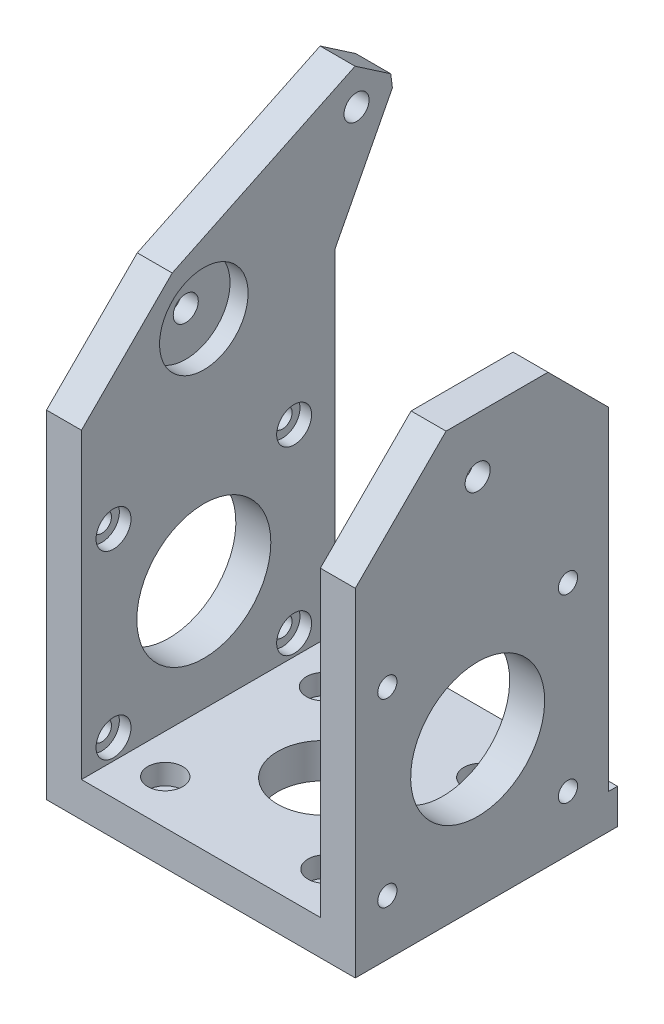
SolidWorks part; units mm, degrees
ref_plane "前视基准面" through (0, 0, 0) normal (0, 0, 1) x (1, 0, 0)
ref_plane "上视基准面" through (0, 0, 0) normal (0, 1, 0) x (1, 0, 0)
ref_plane "右视基准面" through (0, 0, 0) normal (1, 0, 0) x (0, 0, -1)
sketch "草图1" plane through (0, 0, 0) normal (0, 0, 1) x (1, 0, 0)
  line L0 (0, 69.1122) -> (0, -33.2959) construction
  line L1 (-20.5, 73.5) -> (-26.5, 73.5)
  line L2 (-26.5, 73.5) -> (-26.5, 0)
  line L3 (-26.5, 0) -> (26.5, 0)
  line L4 (-20.5, 73.5) -> (-20.5, 6)
  line L5 (-20.5, 6) -> (20.5, 6)
  line L6 (20.5, 73.5) -> (20.5, 6)
  line L7 (26.5, 73.5) -> (26.5, 0)
  line L8 (20.5, 73.5) -> (26.5, 73.5)
  point P10 (0, 6)
  point P12 (0, 0)
  dimension "D1" = 53
  dimension "D2" = 73.5
  dimension "D3" = 6
  dimension "D4" = 6
  dimension "D5" = 41
extrude "凸台-拉伸1" add sketch "草图1" along normal blind 64
sketch "草图2" plane through (0, 6, 0) normal (0, 1, 0) x (1, 0, 0)
  line L0 (0, -64) -> (0, 9.0093) construction
  line L1 (20.5, -64) -> (-20.5, -64) construction
  line L2 (-37.6795, -29.6523) -> (44.7155, -30.4126) construction
  circle A0 centre (0, -30) radius 7.85
  circle A1 centre (-13.5, -16.3749) radius 1.65
  circle A2 centre (-13.7491, -43.3737) radius 1.65
  circle A3 centre (13.7491, -43.3737) radius 1.65
  circle A4 centre (13.5, -16.3749) radius 1.65
  dimension "D1" = 34
  dimension "D2" = 15.7
  dimension "D3" = 27
  dimension "D4" = 3.3
  dimension "D5" = 27
extrude "切除-拉伸1" cut sketch "草图2" against normal blind 20
sketch "草图3" plane through (0, 6, 0) normal (0, 1, 0) x (1, 0, 0)
  circle A0 centre (-13.5, -16.3749) radius 3
  circle A1 centre (13.5, -16.3749) radius 3
  circle A2 centre (13.7491, -43.3737) radius 3
  circle A3 centre (-13.7491, -43.3737) radius 3
  dimension "D1" = 6
extrude "切除-拉伸2" cut sketch "草图3" against normal blind 3.5
sketch "草图4" plane through (26.5, 0, 0) normal (1, 0, 0) x (0, 0, -1)
  line L1 (-64, 0) -> (-64, 73.5) construction
  line L4 (-51, 0) -> (-51, 57.9226)
  line L5 (-51, 57.9226) -> (-35.4226, 73.5)
  line L6 (-64, 73.5) -> (0, 73.5) construction
  line L7 (-35.4226, 73.5) -> (-17.9226, 73.5)
  line L8 (-17.9226, 73.5) -> (-7.5, 63.0774)
  line L9 (-6, 6) -> (-6, 0)
  line L10 (-7.5, 63.0774) -> (-7.5, 6)
  line L11 (-64, 0) -> (0, 0) construction
  line L13 (0, 0) -> (0, 73.5)
  line L14 (0, 0) -> (0, 73.5) construction
  line L15 (0, 73.5) -> (-17.9226, 73.5)
  line L16 (-64, 0) -> (-64, 73.5)
  line L17 (-64, 73.5) -> (-35.4226, 73.5)
  line L23 (-6, 0) -> (0, 0)
  line L25 (-53.2092, 0) -> (-64, 0)
  line L26 (-6, 6) -> (-7.5, 6)
  dimension "D1" = 13
  dimension "D6" = 43.5
  dimension "D7" = 17.5
  dimension "D8" = 45
  dimension "D9" = 45
  dimension "D10" = 28.5774
extrude "切除-拉伸3" cut sketch "草图4" against normal through all
sketch "草图5" plane through (26.5, 0, 0) normal (1, 0, 0) x (0, 0, -1)
  line L0 (-51, 0) -> (-51, 57.9226) construction
  line L1 (-51, 0) -> (-6, 0) construction
  line L2 (-30, 72.1014) -> (-30, -4.8717) construction
  line L3 (-57.7657, 25) -> (11.8561, 25) construction
  line L4 (-35.4226, 73.5) -> (-17.9226, 73.5) construction
  circle A0 centre (-30, 25) radius 11.5
  circle A1 centre (-45.5, 9.5) radius 1.65
  circle A2 centre (-14.5, 9.5) radius 1.65
  circle A3 centre (-14.5, 40.5) radius 1.65
  circle A4 centre (-45.5, 40.5) radius 1.65
  circle A5 centre (-30, 64) radius 2.15
  dimension "D1" = 23
  dimension "D2" = 21
  dimension "D3" = 25
  dimension "D4" = 3.3
  dimension "D5" = 31
  dimension "D6" = 31
  dimension "D7" = 4.3
  dimension "D8" = 9.5
extrude "切除-拉伸4" cut sketch "草图5" against normal through all
sketch "草图6" plane through (-20.5, 0, 0) normal (1, 0, 0) x (0, 0, -1)
  circle A0 centre (-30, 64) radius 7.6
  dimension "D1" = 15.2
extrude "切除-拉伸5" cut sketch "草图6" against normal offset from surface (3.1 mm away) 2.9 up to face at (-26.5, 66.15, 30)
sketch "草图7" plane through (20.5, 0, 0) normal (-1, 0, 0) x (0, 0, 1)
  circle A0 centre (30, 64) radius 7.6
  dimension "D1" = 15.2
extrude "切除-拉伸6" cut sketch "草图7" against normal offset from surface (3.1 mm away) 2.9 up to face at (26.5, 66.15, 30)
sketch "草图10" plane through (-26.5, 0, 0) normal (-1, 0, 0) x (0, 0, 1)
  line L5 (35.4226, 73.5) -> (4.0421, 88.5541)
  line L11 (4.0421, 88.5541) -> (-2.0825, 84.3666)
  line L12 (-2.3695, 82.1357) -> (7.5, 63.0774)
  line L13 (7.5, 63.0774) -> (17.9226, 73.5)
  line L14 (17.9226, 73.5) -> (35.4226, 73.5)
  line L15 (30, 64) -> (3.7871, 82.3544) construction
  line L16 (30, 64) -> (-10.525, 64) construction
  line L17 (0.9798, 86.4603) -> (11.3238, 71.3317) construction
  line L18 (-2.3695, 82.1357) -> (-2.0825, 84.3666)
  circle A1 centre (3.7871, 82.3544) radius 2.15
  circle A2 centre (30, 64) radius 2.15 construction
  dimension "D2" = 32
  dimension "D1" = 4.3
  dimension "D3" = 35
extrude "凸台-拉伸3" add sketch "草图10" against normal up to surface (6 mm away) up to face at (-20.5, 71.6, 30)
sketch "草图11" plane through (-20.5, 0, 0) normal (1, 0, 0) x (0, 0, -1)
  circle A0 centre (-45.5, 40.5) radius 3
  circle A1 centre (-14.5, 40.5) radius 3
  circle A2 centre (-45.5, 9.5) radius 3
  circle A3 centre (-14.5, 9.5) radius 3
  dimension "D1" = 6
extrude "切除-拉伸7" cut sketch "草图11" against normal blind 2
sketch "草图12" plane through (20.5, 0, 0) normal (-1, 0, 0) x (0, 0, 1)
  circle A0 centre (14.5, 40.5) radius 3
  circle A1 centre (45.5, 40.5) radius 3
  circle A2 centre (45.5, 9.5) radius 3
  circle A3 centre (14.5, 9.5) radius 3
  dimension "D1" = 6
extrude "切除-拉伸8" cut sketch "草图12" against normal blind 2
